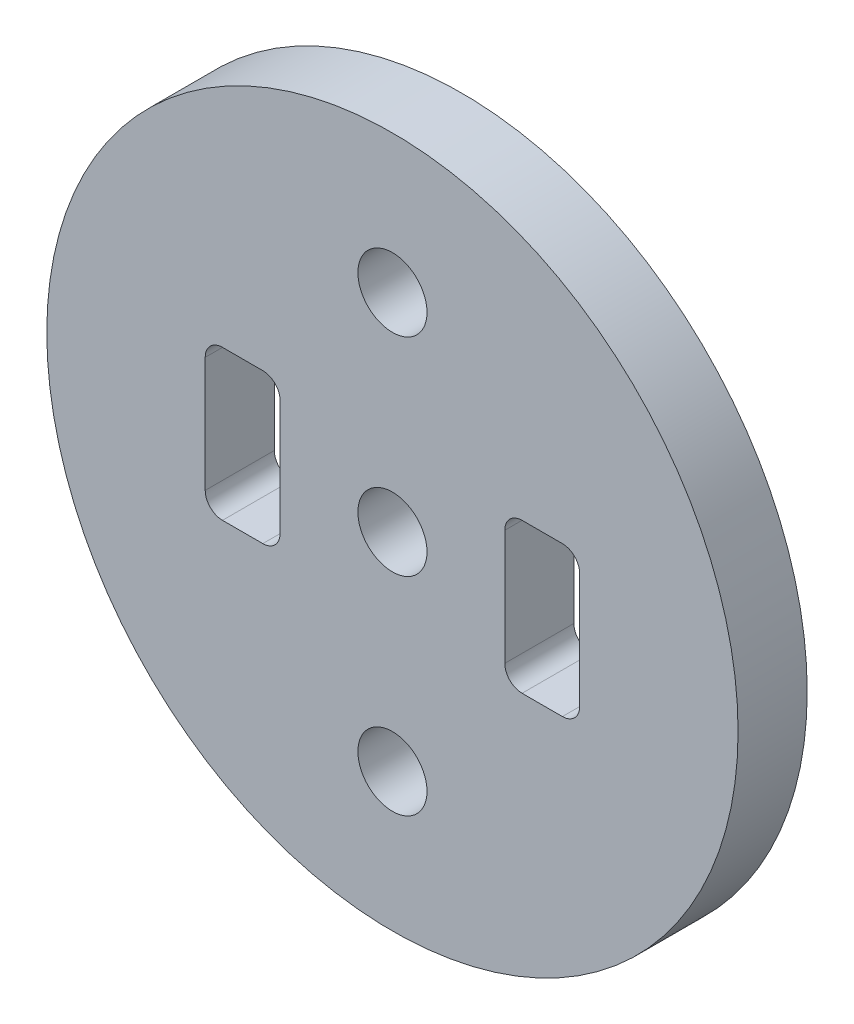
SolidWorks part; units mm, degrees
ref_plane "Alzado" through (0, 0, 0) normal (0, 0, 1) x (1, 0, 0)
ref_plane "Planta" through (0, 0, 0) normal (0, 1, 0) x (1, 0, 0)
ref_plane "Vista lateral" through (0, 0, 0) normal (1, 0, 0) x (0, 0, -1)
sketch "Model" plane through (0, 0, 0) normal (0, 0, 1) x (1, 0, 0)
  line L0 (223.1228, 245.202) -> (221.3728, 245.202)
  line L1 (223.8728, 239.452) -> (223.8728, 244.452)
  line L2 (221.3728, 238.702) -> (223.1228, 238.702)
  line L3 (220.6228, 244.452) -> (220.6228, 239.452)
  line L4 (208.3728, 245.202) -> (210.1228, 245.202)
  line L5 (207.6228, 239.452) -> (207.6228, 244.452)
  line L6 (210.1228, 238.702) -> (208.3728, 238.702)
  line L7 (210.8728, 244.452) -> (210.8728, 239.452)
  circle A0 centre (215.7478, 241.952) radius 1.5
  circle A1 centre (215.7478, 232.952) radius 1.5
  circle A2 centre (215.7478, 250.952) radius 1.5
  arc A3 (221.3728, 245.202) -> (220.6228, 244.452) centre (221.3728, 244.452) ccw
  arc A4 (223.8728, 244.452) -> (223.1228, 245.202) centre (223.1228, 244.452) ccw
  arc A5 (223.1228, 238.702) -> (223.8728, 239.452) centre (223.1228, 239.452) ccw
  arc A6 (220.6228, 239.452) -> (221.3728, 238.702) centre (221.3728, 239.452) ccw
  arc A7 (210.8728, 244.452) -> (210.1228, 245.202) centre (210.1228, 244.452) ccw
  arc A8 (208.3728, 245.202) -> (207.6228, 244.452) centre (208.3728, 244.452) ccw
  arc A9 (207.6228, 239.452) -> (208.3728, 238.702) centre (208.3728, 239.452) ccw
  arc A10 (210.1228, 238.702) -> (210.8728, 239.452) centre (210.1228, 239.452) ccw
  circle A11 centre (215.7478, 241.952) radius 15
extrude "Saliente-Extruir1" add sketch "Model" along normal blind 3
